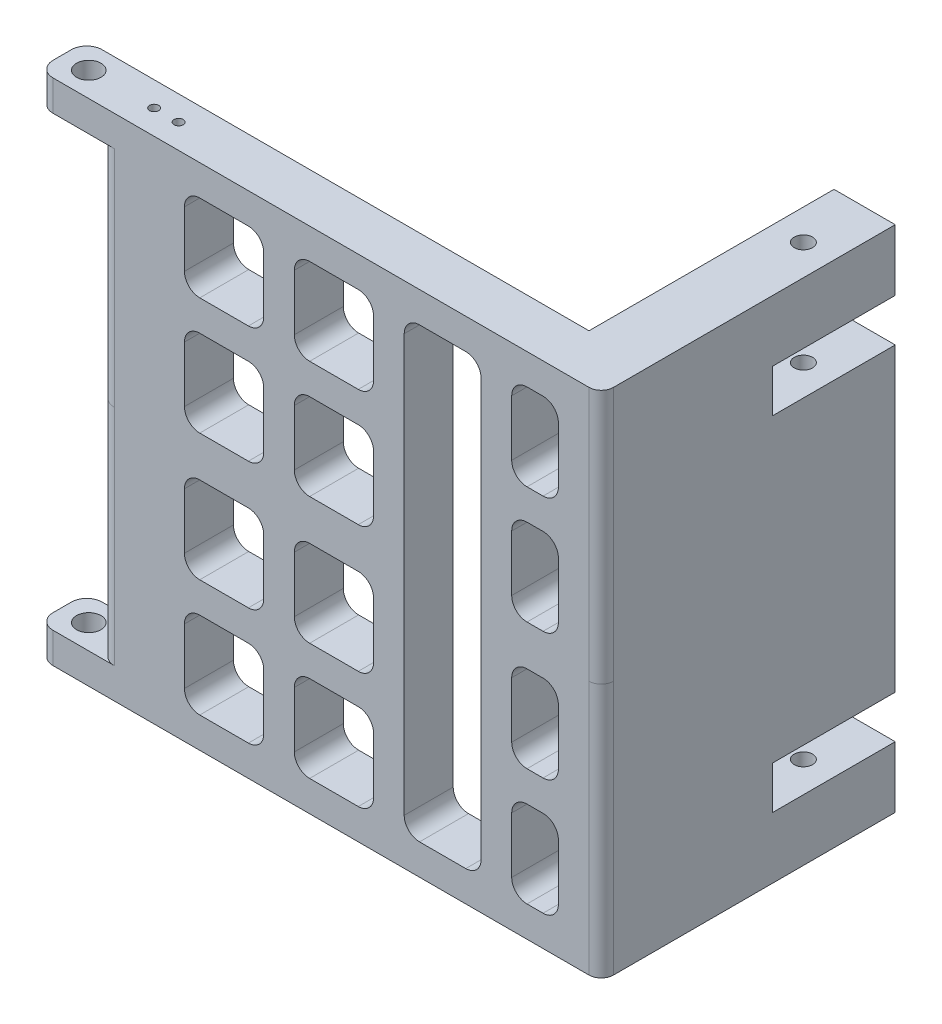
SolidWorks part; units mm, degrees
material "ABS"
ref_plane "Plano frontal" through (0, 0, 0) normal (0, 0, 1) x (1, 0, 0)
ref_plane "Plano superior" through (0, 0, 0) normal (0, 1, 0) x (1, 0, 0)
ref_plane "Plano direito" through (0, 0, 0) normal (1, 0, 0) x (0, 0, -1)
sketch "Esboço2" plane through (0, 0, 0) normal (0, 0, 1) x (1, 0, 0)
  line L1 (-67.2812, 6.4424) -> (14.7188, 6.4424)
  line L2 (-67.2812, 6.4424) -> (-67.2812, -35.1076)
  line L3 (-67.2812, -35.1076) -> (14.7188, -35.1076)
  line L4 (14.7188, 6.4424) -> (14.7188, -35.1076)
extrude "Ressalto-extrusão1" add sketch "Esboço2" along normal blind 8
sketch "Esboço3" plane through (0, -35.1076, 0) normal (0, -1, 0) x (-1, 0, 0)
  line L0 (50.5731, -0.27) -> (50.5731, -7.73) construction
  line L1 (50.5731, -7.73) -> (50.1981, -7.73) construction
  line L3 (54.6594, -4) -> (67.2812, -4) construction
  line L4 (67.2812, -8) -> (67.2812, 0) construction
  line L5 (67.2812, 0) -> (-14.7188, 0) construction
  line L7 (50.5731, -7.73) -> (50.9481, -7.73) construction
  circle A5 centre (58.2812, -4) radius 0.75
  circle A7 centre (62.2812, -4) radius 0.75
  dimension "D1" = 5
  dimension "D7" = 7.46
  dimension "D8" = 0.27
  dimension "D9" = 0
extrude "Corte-extrusão1" cut sketch "Esboço3" against normal through all
sketch "Esboço7" plane through (14.7188, 0, 0) normal (1, 0, 0) x (0, 0, -1)
  line L1 (0, 6.4424) -> (40, 6.4424)
  line L2 (0, 6.4424) -> (0, -35.1076)
  line L3 (0, -35.1076) -> (40, -35.1076)
  line L4 (40, 6.4424) -> (40, -35.1076)
extrude "Ressalto-extrusão2" add sketch "Esboço7" against normal blind 10
fillet "Filete1" radius 2 1 edges at (14.7188, -14.3326, 8)
sketch "Esboço11" plane through (0, 0, 8) normal (0, 0, 1) x (1, 0, 0)
  line L0 (-67.2812, 3.1324) -> (12.7188, 3.1324) construction
  line L1 (-67.2812, -35.1076) -> (12.7188, -35.1076) construction
  line L2 (12.7188, -35.1076) -> (12.7188, 6.4424) construction
  line L3 (12.7188, 6.4424) -> (-67.2812, 6.4424) construction
  line L4 (-62.2812, -35.1076) -> (-62.2812, 6.4424) construction
  line L5 (-67.2812, -35.1076) -> (12.7188, -35.1076) construction
  line L6 (7.7188, -35.1076) -> (7.7188, 6.4424) construction
  line L7 (-67.2812, -30.1076) -> (12.7188, -30.1076) construction
  line L13 (-67.2812, 6.4424) -> (-67.2812, -35.1076) construction
  line L17 (-50.8312, -30.1076) -> (-42.8912, -30.1076)
  line L18 (-53.3312, -27.6076) -> (-53.3312, -18.4876)
  line L19 (-50.8312, -15.9876) -> (-42.8912, -15.9876)
  line L20 (-40.3912, -27.6076) -> (-40.3912, -18.4876)
  line L21 (-50.8312, 3.1324) -> (-42.8912, 3.1324)
  line L22 (-53.3312, 0.6324) -> (-53.3312, -8.4876)
  line L23 (-50.8312, -10.9876) -> (-42.8912, -10.9876)
  line L24 (-40.3912, 0.6324) -> (-40.3912, -8.4876)
  line L25 (5.2188, 3.1324) -> (2.5988, 3.1324)
  line L26 (7.7188, 0.6324) -> (7.7188, -8.4876)
  line L27 (5.2188, -10.9876) -> (2.5988, -10.9876)
  line L28 (0.0988, 0.6324) -> (0.0988, -8.4876)
  line L29 (5.2188, -30.1076) -> (2.5988, -30.1076)
  line L30 (7.7188, -27.6076) -> (7.7188, -18.4876)
  line L31 (5.2188, -15.9876) -> (2.5988, -15.9876)
  line L32 (0.0988, -27.6076) -> (0.0988, -18.4876)
  line L33 (-4.9012, 6.4424) -> (-17.4512, 6.4424)
  line L34 (-4.9012, 6.4424) -> (-4.9012, -27.6076)
  line L35 (-7.4012, -30.1076) -> (-14.9512, -30.1076)
  line L36 (-17.4512, 6.4424) -> (-17.4512, -27.6076)
  line L37 (-32.8912, -30.1076) -> (-24.9512, -30.1076)
  line L38 (-35.3912, -27.6076) -> (-35.3912, -18.4876)
  line L39 (-32.8912, -15.9876) -> (-24.9512, -15.9876)
  line L40 (-22.4512, -27.6076) -> (-22.4512, -18.4876)
  line L41 (-32.8912, 3.1324) -> (-24.9512, 3.1324)
  line L42 (-35.3912, 0.6324) -> (-35.3912, -8.4876)
  line L43 (-32.8912, -10.9876) -> (-24.9512, -10.9876)
  line L44 (-22.4512, 0.6324) -> (-22.4512, -8.4876)
  arc A0 (-14.9512, -30.1076) -> (-17.4512, -27.6076) centre (-14.9512, -27.6076) cw
  arc A1 (-7.4012, -30.1076) -> (-4.9012, -27.6076) centre (-7.4012, -27.6076) ccw
  arc A2 (7.7188, -8.4876) -> (5.2188, -10.9876) centre (5.2188, -8.4876) cw
  arc A3 (5.2188, 3.1324) -> (7.7188, 0.6324) centre (5.2188, 0.6324) cw
  arc A4 (2.5988, 3.1324) -> (0.0988, 0.6324) centre (2.5988, 0.6324) ccw
  arc A5 (2.5988, -10.9876) -> (0.0988, -8.4876) centre (2.5988, -8.4876) cw
  arc A6 (7.7188, -18.4876) -> (5.2188, -15.9876) centre (5.2188, -18.4876) ccw
  arc A7 (5.2188, -30.1076) -> (7.7188, -27.6076) centre (5.2188, -27.6076) ccw
  arc A8 (2.5988, -30.1076) -> (0.0988, -27.6076) centre (2.5988, -27.6076) cw
  arc A9 (2.5988, -15.9876) -> (0.0988, -18.4876) centre (2.5988, -18.4876) ccw
  arc A10 (-24.9512, -30.1076) -> (-22.4512, -27.6076) centre (-24.9512, -27.6076) ccw
  arc A11 (-24.9512, -15.9876) -> (-22.4512, -18.4876) centre (-24.9512, -18.4876) cw
  arc A12 (-32.8912, -30.1076) -> (-35.3912, -27.6076) centre (-32.8912, -27.6076) cw
  arc A13 (-35.3912, -18.4876) -> (-32.8912, -15.9876) centre (-32.8912, -18.4876) cw
  arc A14 (-24.9512, -10.9876) -> (-22.4512, -8.4876) centre (-24.9512, -8.4876) ccw
  arc A15 (-24.9512, 3.1324) -> (-22.4512, 0.6324) centre (-24.9512, 0.6324) cw
  arc A16 (-32.8912, 3.1324) -> (-35.3912, 0.6324) centre (-32.8912, 0.6324) ccw
  arc A17 (-35.3912, -8.4876) -> (-32.8912, -10.9876) centre (-32.8912, -8.4876) ccw
  arc A18 (-42.8912, 3.1324) -> (-40.3912, 0.6324) centre (-42.8912, 0.6324) cw
  arc A19 (-50.8312, 3.1324) -> (-53.3312, 0.6324) centre (-50.8312, 0.6324) ccw
  arc A20 (-42.8912, -10.9876) -> (-40.3912, -8.4876) centre (-42.8912, -8.4876) ccw
  arc A21 (-53.3312, -18.4876) -> (-50.8312, -15.9876) centre (-50.8312, -18.4876) cw
  arc A22 (-42.8912, -15.9876) -> (-40.3912, -18.4876) centre (-42.8912, -18.4876) cw
  arc A23 (-42.8912, -30.1076) -> (-40.3912, -27.6076) centre (-42.8912, -27.6076) ccw
  arc A24 (-50.8312, -30.1076) -> (-53.3312, -27.6076) centre (-50.8312, -27.6076) cw
  arc A25 (-53.3312, -8.4876) -> (-50.8312, -10.9876) centre (-50.8312, -8.4876) ccw
  point P35 (0.0988, 3.1324)
  point P41 (-17.4512, -30.1076)
  point P54 (7.7188, 3.1324)
  point P69 (0.0988, -23.0476)
  point P79 (-35.3912, -30.1076)
  point P88 (-35.3912, 3.1324)
  point P95 (-53.3312, 3.1324)
  point P100 (-53.3312, -15.9876)
  point P103 (-40.3912, -15.9876)
  point P108 (-53.3312, -30.1076)
  dimension "D8" = 5
  dimension "D7" = 5
  dimension "D3" = 5
  dimension "D4" = 5
  dimension "D6" = 5
  dimension "D15" = 44.83
  dimension "D16" = 5
  dimension "D17" = 5
  dimension "D18" = 5
  dimension "D19" = 5
  dimension "D20" = 5
  dimension "D21" = 5
extrude "Corte-extrusão3" cut sketch "Esboço11" against normal blind 8 and the other way through all
sketch "Esboço12" plane through (14.7188, 0, 0) normal (1, 0, 0) x (0, 0, -1)
  line L0 (40, -35.1076) -> (40, 6.4424) construction
  line L1 (40, -25.1076) -> (20, -25.1076)
  line L2 (40, -25.1076) -> (40, -18.1076)
  line L3 (40, -18.1076) -> (20, -18.1076)
  line L4 (20, -25.1076) -> (20, -18.1076)
  line L5 (-6, -35.1076) -> (40, -35.1076) construction
  dimension "D1" = 10
extrude "Corte-extrusão4" cut sketch "Esboço12" against normal blind 10
sketch "Esboço17" plane through (0, 0, 0) normal (0, 0, -1) x (-1, 0, 0)
  line L1 (67.2812, -35.1076) -> (77.2812, -35.1076)
  line L2 (67.2812, -35.1076) -> (67.2812, -30.1076)
  line L3 (67.2812, -30.1076) -> (77.2812, -30.1076)
  line L4 (77.2812, -35.1076) -> (77.2812, -30.1076)
sketch "Esboço19" plane through (0, -35.1076, 0) normal (0, -1, 0) x (1, 0, 0)
  line L0 (4.7188, 0) -> (4.7188, -40) construction
  line L1 (4.7188, -40) -> (14.7188, -40) construction
  circle A0 centre (9.7188, -30) radius 1.5
  dimension "D1" = 5
  dimension "D2" = 10
extrude "Corte-extrusão7" cut sketch "Esboço19" against normal through all
extrude "Ressalto-extrusão4" add sketch "Esboço17" against normal blind 8
sketch "Esboço20" plane through (0, -35.1076, 0) normal (0, -1, 0) x (1, 0, 0)
  line L0 (-77.2812, 8) -> (12.7188, 8) construction
  circle A0 centre (-72.9512, 4) radius 2
  circle A1 centre (-62.2812, 4) radius 0.75 construction
  dimension "D1" = 4
  dimension "D2" = 10.67
extrude "Corte-extrusão9" cut sketch "Esboço20" against normal blind 8 contours A0
fillet "Filete2" radius 2.5 1 edges at (-67.2812, -11.8326, 8)
fillet "Filete3" radius 2.5 1 edges at (-67.2812, -11.8326, 0)
fillet "Filete4" radius 2.5 1 edges at (-77.2812, -32.6076, 8)
fillet "Filete5" radius 2.5 1 edges at (-77.2812, -32.6076, 0)
ref_plane "Plano1" through (0, 6.4424, 0) normal (0, 1, 0) x (1, 0, 0)
mirror "Espelhar5" about plane through (0, 6.4424, 0) normal (0, 1, 0) of "Ressalto-extrusão1", "Corte-extrusão1", "Ressalto-extrusão2", "Filete1", "Corte-extrusão3", "Corte-extrusão4", "Corte-extrusão7", "Ressalto-extrusão4", "Corte-extrusão9", "Filete2", "Filete3", "Filete4", "Filete5"
